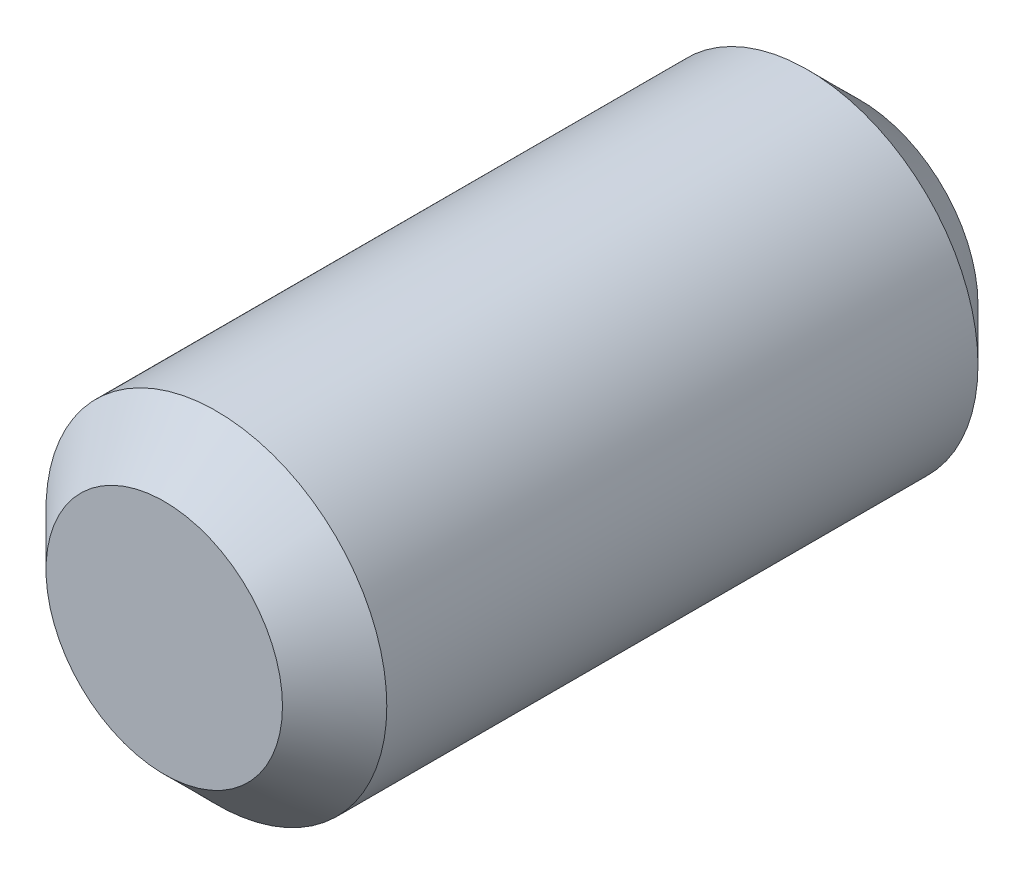
SolidWorks part; units mm, degrees
ref_plane "Front Plane" through (0, 0, 0) normal (0, 0, 1) x (1, 0, 0)
ref_plane "Top Plane" through (0, 0, 0) normal (0, 1, 0) x (1, 0, 0)
ref_plane "Right Plane" through (0, 0, 0) normal (1, 0, 0) x (0, 0, -1)
sketch "Sketch1" plane through (0, 0, 0) normal (0, 0, 1) x (1, 0, 0)
  circle A0 centre (0, 0) radius 2.45
extrude "Boss-Extrude1" add sketch "Sketch1" along normal blind 10 contours A0
fillet "Fillet1" radius 0.75 2 edges at (2.45, 0, 0) (2.45, 0, 10) profile chamfer
